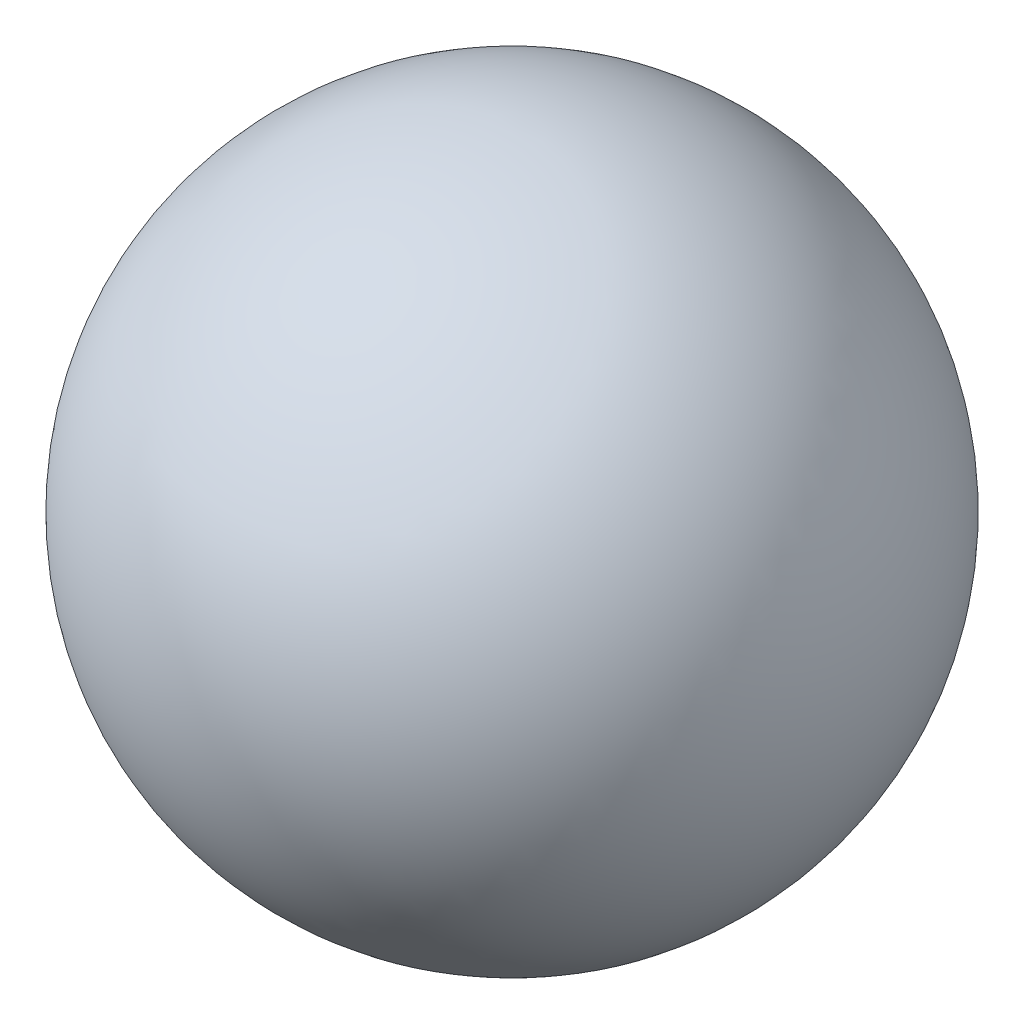
SolidWorks part; units mm, degrees
ref_plane "Front" through (0, 0, 0) normal (0, 0, 1) x (1, 0, 0)
ref_plane "Top" through (0, 0, 0) normal (0, 1, 0) x (1, 0, 0)
ref_plane "Right" through (0, 0, 0) normal (1, 0, 0) x (0, 0, -1)
sketch "Sketch2" plane through (0, 0, 0) normal (1, 0, 0) x (0, 0, -1)
  line L0 (0, -2.25) -> (0, 2.25)
  circle A0 centre (0, 0) radius 2.25 construction
  arc A1 (0, 2.25) -> (0, -2.25) centre (0, 0) cw
  dimension "D1" = 4.5
revolve "Revolve1" add sketch "Sketch2" angle 360 about L0
sketch "Bearing Slot Cut Guide Loose" plane through (0, 0, 0) normal (1, 0, 0) x (0, 0, -1)
  line L0 (-1.1013, 2.35) -> (1.1013, 2.35)
  line L1 (1.1013, 2.35) -> (2.7467, 0)
  line L3 (-1.1013, 2.35) -> (-2.7467, 0)
  line L5 (0, 0) -> (0, 2.35) construction
  line L6 (0, 0) -> (-2.35, 0) construction
  line L7 (-1.1013, -2.35) -> (-2.7467, 0)
  line L8 (-1.1013, -2.35) -> (1.1013, -2.35)
  line L9 (1.1013, -2.35) -> (2.7467, 0)
  circle A3 centre (0, 0) radius 2.35 construction
  circle A5 centre (0, 0) radius 2.25 construction
  circle A6 centre (0, 0) radius 2.25 construction
  circle A7 centre (0, 0) radius 2.35 construction
  circle A8 centre (0, 0) radius 2.25 construction
  point P5 (0, 2.35)
  point P14 (2.35, 0)
  point P17 (2.7467, 0)
  point P20 (-2.7467, 0)
  point P23 (2.7467, 0)
  point P26 (-2.7467, 0)
  dimension "D1" = 4.7
  dimension "D3" = 4.5
  dimension "D2" = 55
sketch "Bearing Slot Cut Guide Tight" plane through (0, 0, 0) normal (1, 0, 0) x (0, 0, -1)
  line L20 (-1.1, 2.35) -> (1.1, 2.35)
  line L21 (-1.1013, 2.35) -> (1.1013, 2.35) construction
  line L22 (1.1, 2.35) -> (2.7455, 0)
  line L23 (2.7455, 0) -> (1.1, -2.35)
  line L24 (-1.1013, -2.35) -> (1.1013, -2.35) construction
  line L25 (1.1, -2.35) -> (-1.1, -2.35)
  line L26 (-1.1, -2.35) -> (-2.7455, 0)
  line L27 (-2.7455, 0) -> (-1.1, 2.35)
  line L28 (-1.1013, 2.35) -> (-2.7467, 0) construction
  line L29 (1.1013, 2.35) -> (2.7467, 0) construction
  line L30 (-1.1013, -2.35) -> (-2.7467, 0) construction
  line L31 (1.1013, -2.35) -> (2.7467, 0) construction
  line L32 (0, 2.35) -> (0, -2.35) construction
  dimension "D2" = 0.001
